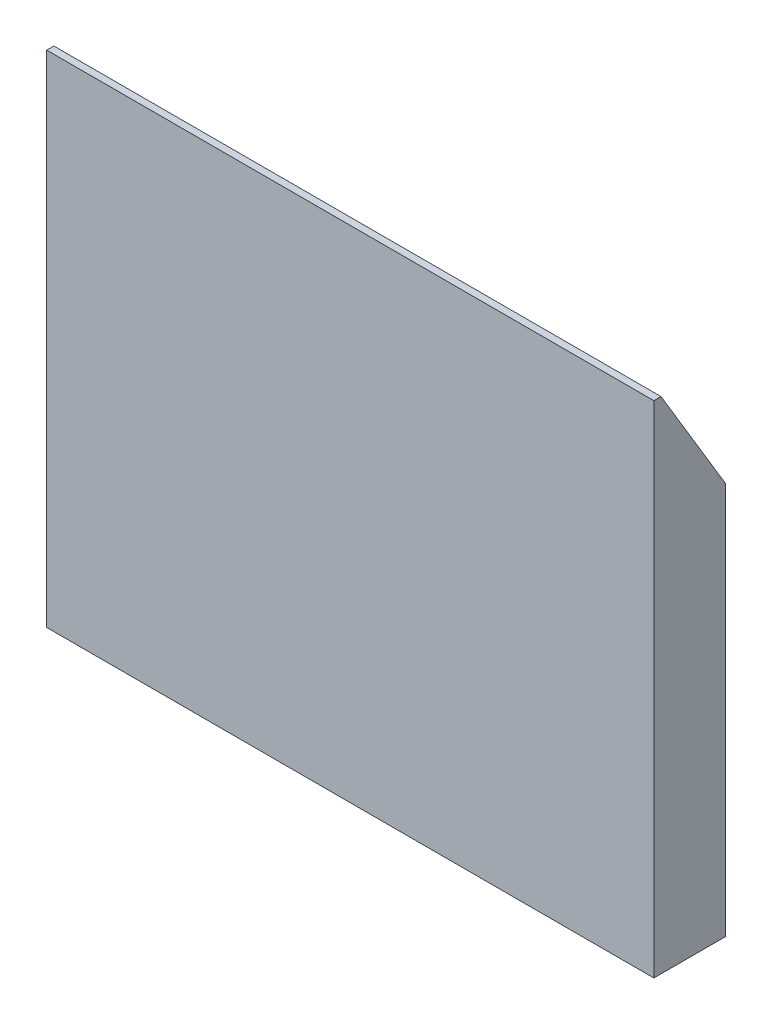
SolidWorks part; units mm, degrees
ref_plane "Front Plane" through (0, 0, 0) normal (0, 0, 1) x (1, 0, 0)
ref_plane "Top Plane" through (0, 0, 0) normal (0, 1, 0) x (1, 0, 0)
ref_plane "Right Plane" through (0, 0, 0) normal (1, 0, 0) x (0, 0, -1)
sketch "Sketch1" plane through (0, 0, 0) normal (0, 1, 0) x (1, 0, 0)
  line L0 (-42.5, 0) -> (42.5, 0)
  line L1 (42.5, 0) -> (42.5, 10)
  line L2 (42.5, 10) -> (41.5, 10)
  line L3 (41.5, 10) -> (41.5, 1)
  line L4 (41.5, 1) -> (-41.5, 1)
  line L5 (-41.5, 1) -> (-41.5, 10)
  line L6 (-41.5, 10) -> (-42.5, 10)
  line L7 (-42.5, 10) -> (-42.5, 0)
  point P4 (0, 0)
  dimension "D1" = 1
  dimension "D2" = 1
  dimension "D3" = 1
  dimension "D4" = 83
  dimension "D5" = 10
  dimension "D6" = 10
extrude "Boss-Extrude1" add sketch "Sketch1" along normal blind 70
sketch "Sketch2" plane through (0, 0, 0) normal (1, 0, 0) x (0, 0, -1)
  line L0 (1, 70) -> (10, 55)
  line L1 (10, 70) -> (10, 0) construction
  line L2 (10, 55) -> (10, 70)
  line L3 (10, 70) -> (1, 70)
  dimension "D1" = 15
  dimension "D2" = 1
extrude "Cut-Extrude2" cut sketch "Sketch2" against normal through all both and the other way through all
